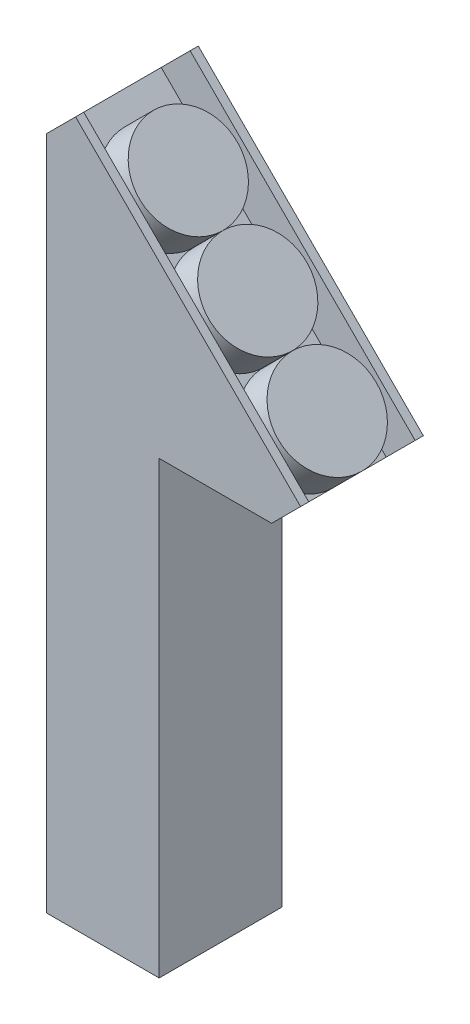
SolidWorks part; units mm, degrees
ref_plane "Front Plane" through (0, 0, 0) normal (0, 0, 1) x (1, 0, 0)
ref_plane "Top Plane" through (0, 0, 0) normal (0, 1, 0) x (1, 0, 0)
ref_plane "Right Plane" through (0, 0, 0) normal (1, 0, 0) x (0, 0, -1)
sketch "Sketch1" plane through (0, 0, 0) normal (0, 0, 1) x (1, 0, 0)
  line L0 (0, 0) -> (0, 55)
  line L1 (0, 55) -> (55, 0)
  line L2 (55, 0) -> (0, 0)
  dimension "D1" = 55
extrude "Boss-Extrude2" add sketch "Sketch1" against normal blind 30
sketch "Sketch2" plane through (27.5, 27.5, 0) normal (0.7071, 0.7071, 0) x (0, 0, -1)
  line L0 (30, -38.8909) -> (0, -38.8909) construction
  line L1 (0, 38.8909) -> (2, 38.8909)
  line L2 (0, 38.8909) -> (0, -38.8909)
  line L3 (0, -38.8909) -> (2, -38.8909)
  line L4 (2, 38.8909) -> (2, -38.8909)
  line L6 (30, 38.8909) -> (28, 38.8909)
  line L7 (30, 38.8909) -> (30, -38.8909)
  line L8 (30, -38.8909) -> (28, -38.8909)
  line L9 (28, 38.8909) -> (28, -38.8909)
  dimension "D1" = 2
  dimension "D2" = 2
extrude "Boss-Extrude3" add sketch "Sketch2" along normal blind 10
sketch "Sketch3" plane through (0, 0, 0) normal (0, -1, 0) x (1, 0, 0)
  line L0 (0, -30) -> (55, -30) construction
  line L1 (0, 0) -> (27.5, 0)
  line L2 (0, 0) -> (0, -30)
  line L3 (0, -30) -> (27.5, -30)
  line L4 (27.5, 0) -> (27.5, -30)
extrude "Boss-Extrude4" add sketch "Sketch3" along normal blind 110
sketch "Sketch4" plane through (27.5, 27.5, 0) normal (0.7071, 0.7071, 0) x (0, 0, -1)
  circle A0 centre (15, -26.8779) radius 12.013
  circle A2 centre (15, -2.8608) radius 12
  circle A3 centre (15, 21.1434) radius 12
  point P0 (0, 0)
  dimension "D1" = 24
  dimension "D2" = 24
extrude "Boss-Extrude8" add sketch "Sketch4" along normal blind 10
